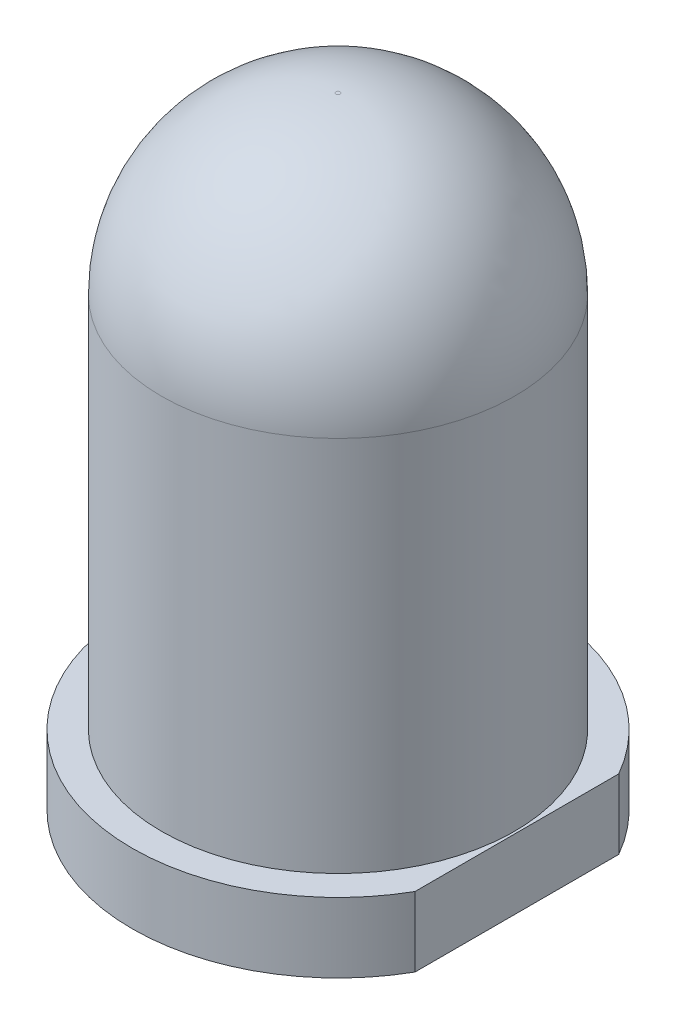
SolidWorks part; units mm, degrees
ref_plane "Front Plane" through (0, 0, 0) normal (0, 0, 1) x (1, 0, 0)
ref_plane "Top Plane" through (0, 0, 0) normal (0, 1, 0) x (1, 0, 0)
ref_plane "Right Plane" through (0, 0, 0) normal (1, 0, 0) x (0, 0, -1)
ref_plane "Plane1" through (0, 0, 0) normal (0, -1, 0) x (1, 0, 0)
sketch "Sketch1" plane through (0, 0, 0) normal (0, -1, 0) x (1, 0, 0)
  line L0 (2.5632, -1.4603) -> (2.5632, 1.4603)
  arc A0 (2.5632, 1.4603) -> (2.5632, -1.4603) centre (0, 0) ccw
extrude "Boss-Extrude1" add sketch "Sketch1" against normal blind 1
ref_plane "Plane2" through (0, 0, 0) normal (0, 0, -1) x (-1, 0, 0)
sketch "Sketch2" plane through (0, 0, 0) normal (0, 0, -1) x (-1, 0, 0)
  line L0 (-2.53, 1) -> (0, 1)
  line L1 (0, 1) -> (0, 8.9)
  line L2 (0, 8.9) -> (-2.53, 8.9)
  line L3 (-2.53, 8.9) -> (-2.53, 1)
  line L4 (0, 1) -> (0, 8.9) construction
revolve "Revolve1" add sketch "Sketch2" angle 360 about L4
fillet "Fillet1" radius 2.5 1 edges at (0, 8.9, 2.53)
